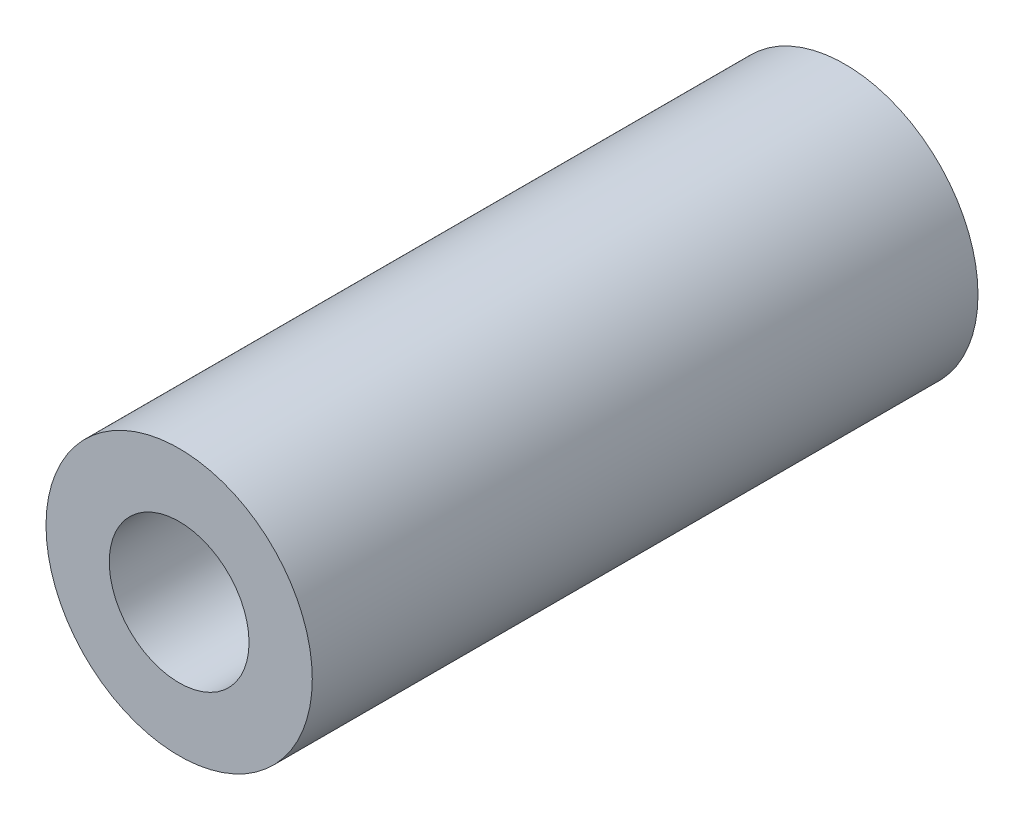
SolidWorks part; units mm, degrees
ref_plane "Front Plane" through (0, 0, 0) normal (0, 0, 1) x (1, 0, 0)
ref_plane "Top Plane" through (0, 0, 0) normal (0, 1, 0) x (1, 0, 0)
ref_plane "Right Plane" through (0, 0, 0) normal (1, 0, 0) x (0, 0, -1)
sketch "Sketch1" plane through (0, 0, 0) normal (0, 0, 1) x (1, 0, 0)
  circle A0 centre (0, 0) radius 4
  circle A1 centre (0, 0) radius 2.1
  dimension "OD" = 8
  dimension "ID" = 4.2
extrude "Extrude1" add sketch "Sketch1" along normal mid plane 20
sketch "Sketch2" plane through (0, 0, 0) normal (1, 0, 0) x (0, 0, -1)
  line L0 (-10, -2.1) -> (10, -2.1) construction
  line L3 (10, 2.1) -> (-10, 2.1) construction
  line L5 (-10, -2.1) -> (10, -2.1)
  line L6 (10, 2.1) -> (-10, 2.1)
sketch "Sketch4" plane through (0, 0, 10) normal (0, 0, 1) x (1, 0, 0)
  line L0 (0, 0) -> (-1.4849, 1.4849)
  line L1 (0, -4.4) -> (0, 4.4) construction
  circle A0 centre (0, 0) radius 2.1 construction
  dimension "D1" = 45
